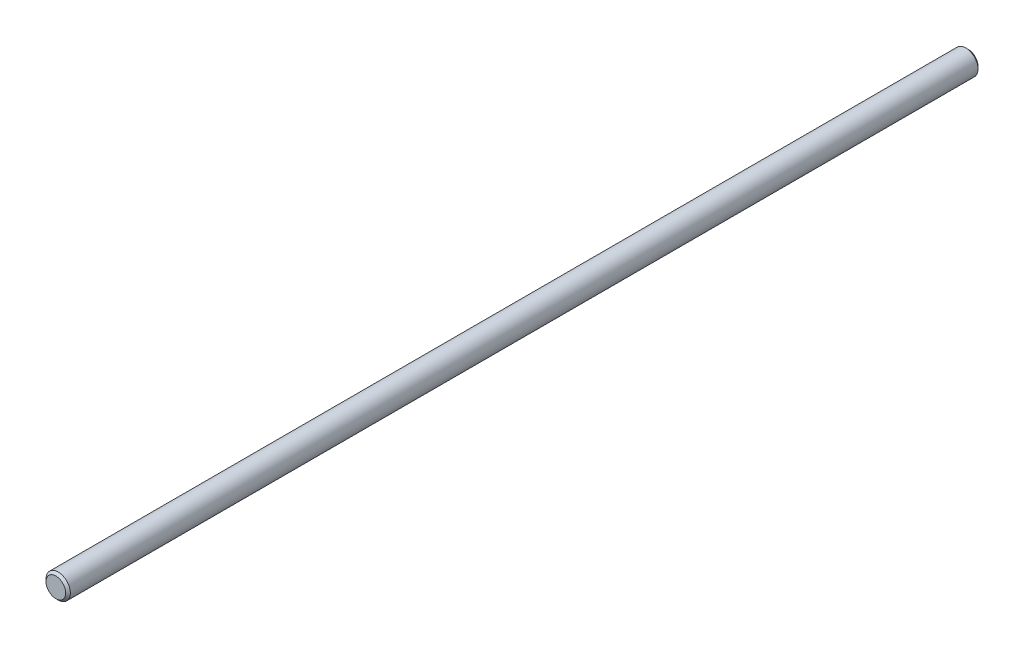
SolidWorks part; units mm, degrees
material "AISI 1045 Steel, cold drawn"
ref_plane "Front Plane" through (0, 0, 0) normal (0, 0, 1) x (1, 0, 0)
ref_plane "Top Plane" through (0, 0, 0) normal (0, 1, 0) x (1, 0, 0)
ref_plane "Right Plane" through (0, 0, 0) normal (1, 0, 0) x (0, 0, -1)
sketch "Sketch1" plane through (0, 0, 0) normal (0, 0, 1) x (1, 0, 0)
  circle A0 centre (0, 0) radius 2
  dimension "D1" = 4
extrude "Boss-Extrude1" add sketch "Sketch1" along normal blind 150
chamfer "Chamfer1" distance 0.381 angle 45 2 edges at (2, 0, 0) (2, 0, 150)
